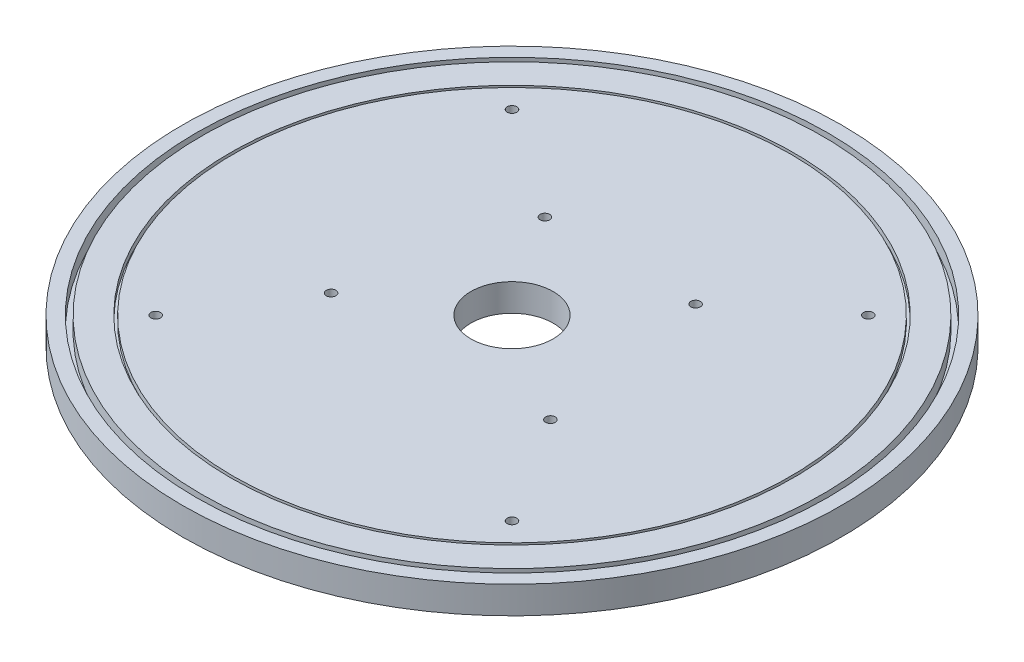
SolidWorks part; units mm, degrees
ref_plane "Plan de face" through (0, 0, 0) normal (0, 0, 1) x (1, 0, 0)
ref_plane "Plan de dessus" through (0, 0, 0) normal (0, 1, 0) x (1, 0, 0)
ref_plane "Plan de droite" through (0, 0, 0) normal (1, 0, 0) x (0, 0, -1)
sketch "Esquisse1" plane through (0, 0, 0) normal (1, 0, 0) x (0, 0, -1)
  line L4 (101.7544, 10) -> (101.7544, 7.8727)
  line L5 (101.7544, 7.8727) -> (102.7544, 7.8727)
  line L6 (102.7544, 7.8727) -> (102.7544, 10)
  line L7 (102.7544, 10) -> (113.2544, 10)
  line L8 (113.2544, 10) -> (113.2544, 5)
  line L9 (113.2544, 5) -> (115.2503, 5)
  line L10 (115.2503, 5) -> (115.2503, 10)
  line L11 (115.2503, 10) -> (120.2543, 10)
  line L12 (120.2543, 10) -> (120.2543, 0)
  line L14 (101.7544, 10) -> (0.0044, 10)
  line L15 (0.0044, 10) -> (0.0044, 0)
  line L16 (120.2543, 0) -> (0.0044, 0)
revolve "Révolution1" add sketch "Esquisse1" angle 360 about L15
sketch "Esquisse3" plane through (0, 10, 0) normal (0, 1, 0) x (1, 0, 0)
  circle A0 centre (0, 0) radius 15
extrude "Enlèv. mat.-Extru.1" cut sketch "Esquisse3" against normal blind 10
sketch "Esquisse4" plane through (0, 0, 0) normal (0, -1, 0) x (1, 0, 0)
  circle A0 centre (-25, -37) radius 1.75
  circle A1 centre (-40, 26) radius 1.75
  circle A2 centre (40, 26) radius 1.75
  circle A3 centre (30, -37) radius 1.75
  point P2 (0, 0)
  point P5 (0, 0)
  point P6 (0, 0)
extrude "Enlèv. mat.-Extru.2" cut sketch "Esquisse4" against normal blind 10
sketch "Esquisse5" plane through (0, 0, 0) normal (0, -1, 0) x (1, 0, 0)
  circle A0 centre (-65, 65) radius 1.75
  circle A1 centre (-65, -65) radius 1.75
  circle A2 centre (65, 65) radius 1.75
  circle A3 centre (65, -65) radius 1.75
  point P2 (0, 0)
extrude "Enlèv. mat.-Extru.3" cut sketch "Esquisse5" against normal blind 10
